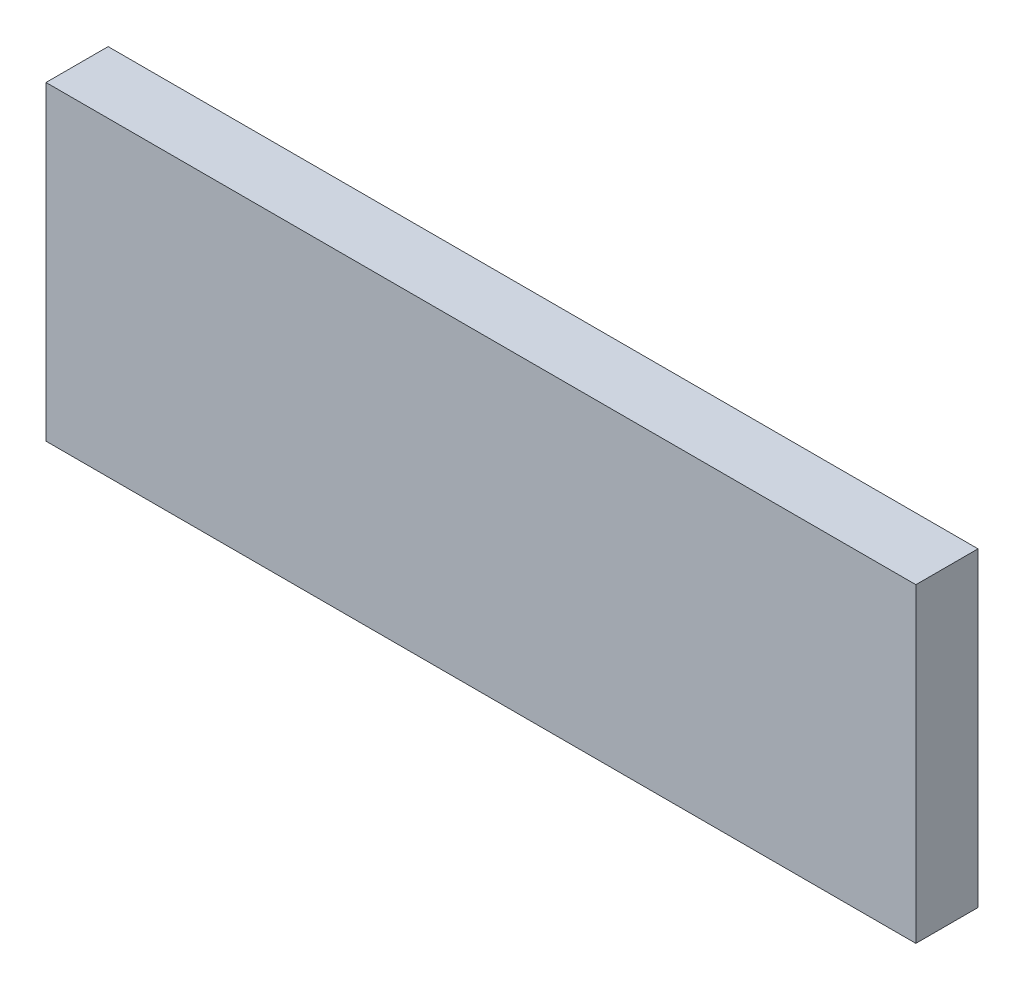
SolidWorks part; units mm, degrees
ref_plane "前视基准面" through (0, 0, 0) normal (0, 0, 1) x (1, 0, 0)
ref_plane "上视基准面" through (0, 0, 0) normal (0, 1, 0) x (1, 0, 0)
ref_plane "右视基准面" through (0, 0, 0) normal (1, 0, 0) x (0, 0, -1)
sketch "草图1" plane through (0, 0, 0) normal (0, 1, 0) x (1, 0, 0)
  line L1 (0, 0) -> (280, 0)
  line L2 (0, 0) -> (0, -20)
  line L3 (0, -20) -> (280, -20)
  line L4 (280, 0) -> (280, -20)
  dimension "D1" = 280
  dimension "D2" = 20
extrude "凸台-拉伸1" add sketch "草图1" along normal blind 100
